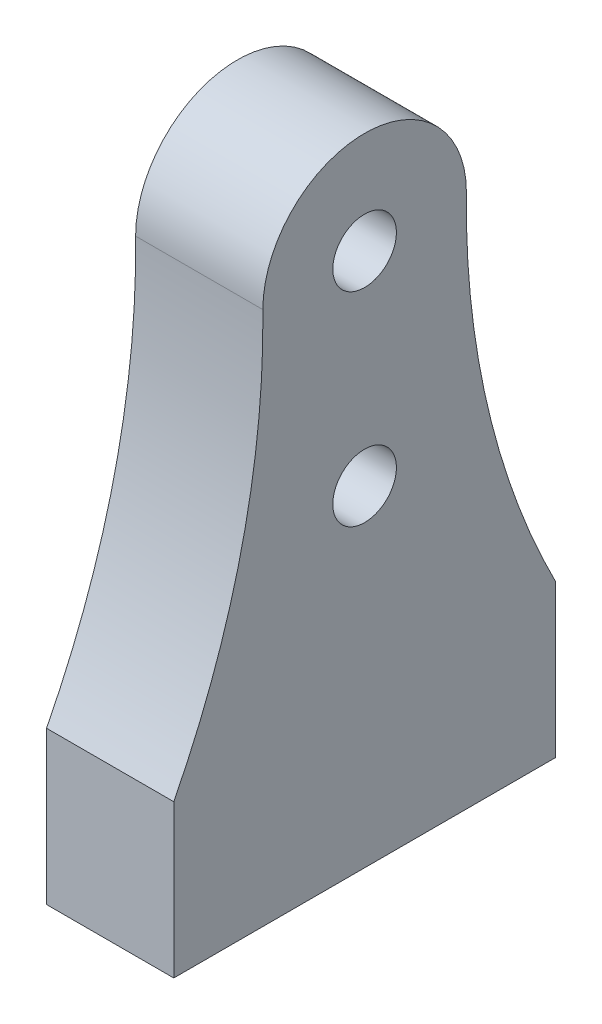
SolidWorks part; units mm, degrees
material "AISI 316 Stainless Steel Sheet (SS)"
ref_plane "Front Plane" through (0, 0, 0) normal (0, 0, 1) x (1, 0, 0)
ref_plane "Top Plane" through (0, 0, 0) normal (0, 1, 0) x (1, 0, 0)
ref_plane "Right Plane" through (0, 0, 0) normal (1, 0, 0) x (0, 0, -1)
sketch "Sketch1" plane through (0, 0, 0) normal (1, 0, 0) x (0, 0, -1)
  line L0 (-7.5, -12.5) -> (7.5, -12.5)
  line L2 (7.5, -12.5) -> (7.5, -6.5)
  line L3 (7.5, -6.5) -> (6, -6.5) construction
  line L4 (6, -6.5) -> (6, 12.5) construction
  line L5 (6, 12.5) -> (-6, 12.5) construction
  line L6 (-6, 12.5) -> (-6, -6.5) construction
  line L7 (-6, -6.5) -> (-7.5, -6.5) construction
  line L8 (-7.5, -6.5) -> (-7.5, -12.5)
  line L9 (0, -12.5) -> (0, 12.5) construction
  line L10 (0, 55) -> (0, -55) construction
  line L12 (55, 0) -> (-55, 0) construction
  arc A2 (-4, 8.5) -> (4, 8.5) centre (0, 8.5) cw
  arc A3 (-7.5, -6.5) -> (-4, 8.5) centre (-35.9969, 8.0576) ccw
  arc A4 (4, 8.5) -> (7.5, -6.5) centre (35.9969, 8.0576) ccw
  point P3 (0, -12.5)
  point P15 (0, 0)
  point P19 (0, 12.5)
  dimension "D6" = 32
  dimension "D1" = 25
  dimension "D2" = 6
  dimension "D3" = 15
  dimension "D4" = 8
  dimension "D5" = 12
extrude "Boss-Extrude1" add sketch "Sketch1" along normal mid plane 5
hole_wizard "Tap Drill for M3 Tap1" positions "Sketch2" profile "Sketch3" hole size "M3" standard "ISO" end condition through all
sketch "Sketch2" plane through (2.5, 0, 0) normal (1, 0, 0) x (0, 0, -1)
  line L1 (0, 2.75) -> (0, -2.75) construction
  line L2 (-7.5, -12.5) -> (7.5, -12.5) construction
  point P0 (0, 8.5)
  point P2 (0, 0.5)
  dimension "D1" = 8
  dimension "D2" = 21
sketch "Sketch3" plane through (2.5, 8.5, 0) normal (0, 1, 0) x (0, 0, -1)
  line L0 (0, 0) -> (0, 5)
  line L1 (0, 5) -> (1.25, 5)
  line L2 (1.25, 5) -> (1.25, 0)
  line L5 (1.25, 0) -> (0, 0)
  line L11 (0, -6.35) -> (0, 107.95) construction
  dimension "Thru Hole Dia." = 2.5
  dimension "Thru Hole Depth" = 5
cosmetic thread "Cosmetic Thread3" parameters "D2"=3
cosmetic thread "Cosmetic Thread4" parameters "D2"=3
hole_wizard "Tap Drill for M3 Tap2" positions "Sketch6" profile "Sketch7" hole size "M3" standard "ISO"
sketch "Sketch6" plane through (0, -12.5, 0) normal (0, -1, 0) x (-1, 0, 0)
  line L0 (-2.75, 0) -> (2.75, 0) construction
  line L1 (0, 8.25) -> (0, -8.25) construction
  point P0 (0, -3.25)
  point P2 (0, 3.25)
  dimension "D1" = 3.25
  dimension "D2" = 6.5
sketch "Sketch7" plane through (0, -12.5, 3.25) normal (1, 0, 0) x (0, 0, -1)
  line L0 (0, 0) -> (0, 5.7511)
  line L1 (0, 5.7511) -> (1.25, 5)
  line L2 (1.25, 5) -> (1.25, 0)
  line L5 (1.25, 0) -> (0, 0)
  line L10 (0, 5.7511) -> (-1.25, 5) construction
  line L11 (0, -6.35) -> (0, 107.95) construction
  dimension "Hole Dia." = 2.5
  dimension "Hole Depth" = 5
  dimension "Drill Angle" = 118
cosmetic thread "Cosmetic Thread1" parameters "D2"=3
cosmetic thread "Cosmetic Thread2" parameters "D2"=3
equation "\"D1@Sketch6\"=\"D2@Sketch6\"/2"
